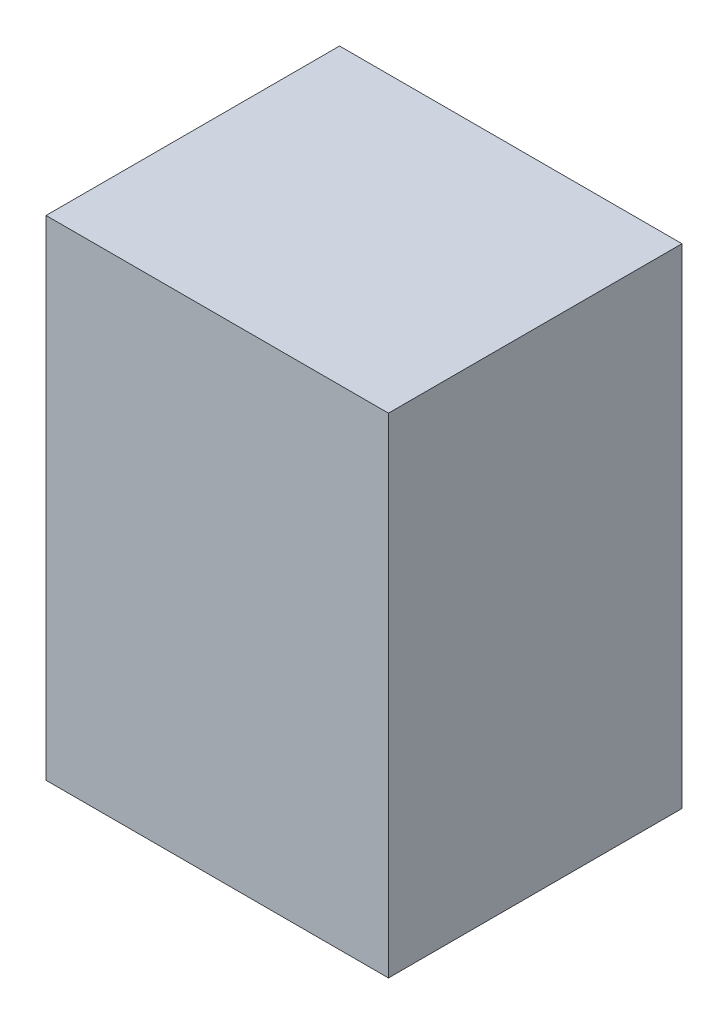
SolidWorks part; units mm, degrees
ref_plane "Front Plane" through (0, 0, 0) normal (0, 0, 1) x (1, 0, 0)
ref_plane "Top Plane" through (0, 0, 0) normal (0, 1, 0) x (1, 0, 0)
ref_plane "Right Plane" through (0, 0, 0) normal (1, 0, 0) x (0, 0, -1)
sketch "Sketch1" plane through (0, 0, 0) normal (0, 0, 1) x (1, 0, 0)
  line L1 (-17.5, 25) -> (17.5, 25)
  line L2 (-17.5, 25) -> (-17.5, -25)
  line L3 (-17.5, -25) -> (17.5, -25)
  line L4 (17.5, 25) -> (17.5, -25)
  line L5 (-17.5, 25) -> (17.5, -25) construction
  line L6 (-17.5, -25) -> (17.5, 25) construction
  point P0 (0, 0)
  dimension "D1" = 50
  dimension "D2" = 35
extrude "Boss-Extrude1" add sketch "Sketch1" along normal blind 30
